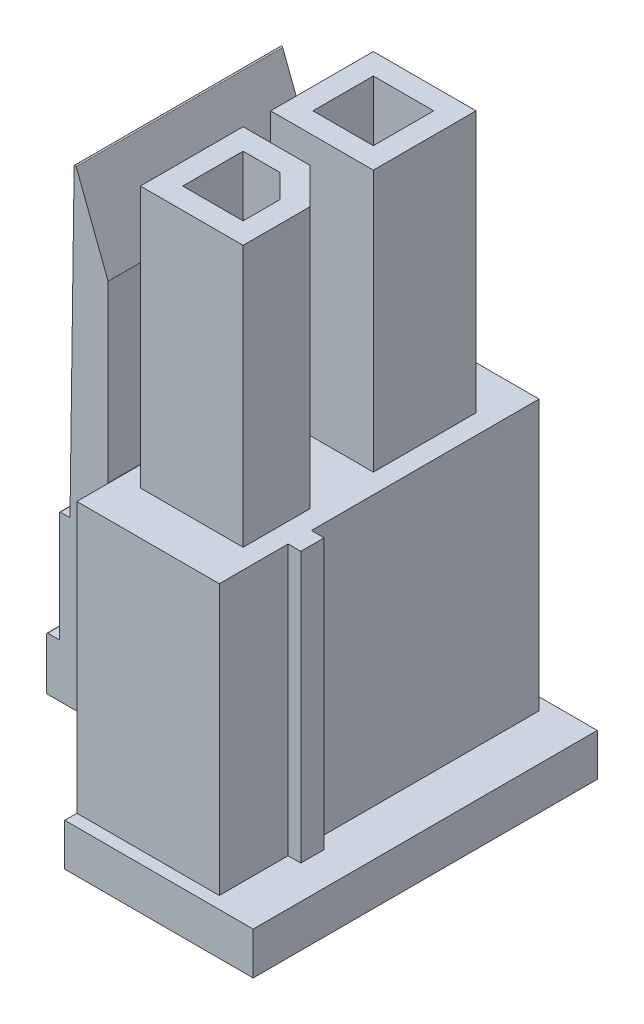
SolidWorks part; units mm, degrees
ref_plane "Front Plane" through (0, 0, 0) normal (0, 0, 1) x (1, 0, 0)
ref_plane "Top Plane" through (0, 0, 0) normal (0, 1, 0) x (1, 0, 0)
ref_plane "Right Plane" through (0, 0, 0) normal (1, 0, 0) x (0, 0, -1)
sketch "Sketch1" plane through (0, 0, 0) normal (0, 0, 1) x (1, 0, 0)
  line L0 (0, 0) -> (3.4163, 0)
  line L1 (3.4163, 0) -> (3.4163, 6.477)
  line L2 (3.4163, 6.477) -> (0, 6.477)
  line L3 (0, 6.477) -> (0, 0)
  dimension "D1" = 3.4163
  dimension "D2" = 6.477
extrude "Extrude1" add sketch "Sketch1" along normal blind 3.8354
mirror "Mirror1" about plane through (0, 0, 3.8354) normal (0, 0, 1) of "Extrude1"
sketch "Sketch2" plane through (3.4163, 0, 0) normal (1, 0, 0) x (0, 0, -1)
  line L0 (-7.6708, 0) -> (0, 0) construction
  line L1 (-6.0198, 0) -> (-5.461, 0)
  line L2 (-6.0198, 0) -> (-6.0198, 6.477)
  line L3 (-6.0198, 6.477) -> (-5.461, 6.477)
  line L4 (-5.461, 0) -> (-5.461, 6.477)
  line L5 (-7.6708, 6.477) -> (0, 6.477) construction
  line L6 (-7.6708, 0) -> (-7.6708, 6.477) construction
  dimension "D1" = 1.651
  dimension "D2" = 0.5588
extrude "Extrude2" add sketch "Sketch2" along normal blind 0.3048
sketch "Sketch3" plane through (0, 0, 0) normal (0, -1, 0) x (1, 0, 0)
  line L0 (0, 7.6708) -> (3.4163, 7.6708) construction
  line L1 (0, -0.2921) -> (4.5212, -0.2921)
  line L2 (0, -0.2921) -> (0, 7.9629)
  line L3 (0, 7.9629) -> (4.5212, 7.9629)
  line L4 (4.5212, -0.2921) -> (4.5212, 7.9629)
  dimension "D1" = 8.255
  dimension "D2" = 4.5212
  dimension "D3" = 0.2921
extrude "Extrude3" add sketch "Sketch3" along normal blind 1.016
sketch "Sketch4" plane through (0, 6.477, 0) normal (0, 1, 0) x (1, 0, 0)
  line L0 (2.4384, -2.9972) -> (0.9906, -2.9972)
  line L1 (2.9464, -6.6294) -> (0.4826, -6.6294)
  line L2 (2.9464, -6.6294) -> (2.9464, -5.0277)
  line L3 (2.0843, -4.1656) -> (0.4826, -4.1656)
  line L4 (0.4826, -6.6294) -> (0.4826, -4.1656)
  line L5 (2.9464, -3.5052) -> (0.4826, -3.5052)
  line L6 (2.9464, -3.5052) -> (2.9464, -1.0414)
  line L7 (2.9464, -1.0414) -> (0.4826, -1.0414)
  line L8 (0.4826, -3.5052) -> (0.4826, -1.0414)
  line L9 (0.9906, -2.9972) -> (0.9906, -1.5494)
  line L10 (0, -7.6708) -> (0, 0) construction
  line L11 (3.4163, 0) -> (0, 0) construction
  line L12 (2.9464, -5.0277) -> (2.0843, -4.1656)
  line L13 (2.4384, -1.5494) -> (0.9906, -1.5494)
  line L14 (2.4384, -2.9972) -> (2.4384, -1.5494)
  line L15 (0.9906, -6.1214) -> (0.9906, -4.6736)
  line L16 (1.8739, -4.6736) -> (0.9906, -4.6736)
  line L17 (2.4384, -5.2381) -> (1.8739, -4.6736)
  line L18 (2.4384, -6.1214) -> (2.4384, -5.2381)
  line L19 (2.4384, -6.1214) -> (0.9906, -6.1214)
  dimension "D1" = 5.588
  dimension "D2" = 2.4638
  dimension "D3" = 2.4638
  dimension "D4" = 0.4826
  dimension "D5" = 1.0414
  dimension "D6" = 1.2192
  dimension "D7" = 0.508
extrude "Extrude4" add sketch "Sketch4" along normal blind 6.2738
sketch "Sketch5" plane through (0, -1.016, 0) normal (0, -1, 0) x (1, 0, 0)
  line L0 (0, -0.2921) -> (4.5212, -0.2921) construction
  line L1 (3.0988, 6.5659) -> (0.635, 6.5659)
  line L2 (3.0988, 6.5659) -> (3.0988, 4.0513)
  line L3 (3.0988, 1.1049) -> (0.635, 1.1049)
  line L4 (0.635, 6.5659) -> (0.635, 4.0513)
  line L6 (3.0988, 4.0513) -> (0.635, 4.0513)
  line L7 (3.0988, 3.6195) -> (0.635, 3.6195)
  line L8 (3.0988, 3.6195) -> (3.0988, 1.1049)
  line L9 (0.635, 3.6195) -> (0.635, 1.1049)
  line L10 (4.5212, -0.2921) -> (4.5212, 7.9629) construction
  dimension "D1" = 5.461
  dimension "D2" = 1.397
  dimension "D3" = 1.4224
  dimension "D4" = 2.4638
  dimension "D5" = 2.5146
  dimension "D6" = 2.5146
extrude "Extrude5" cut sketch "Sketch5" against normal blind 7.2898
ref_plane "Plane1" through (0, 0, 3.8354) normal (0, 0, 1) x (1, 0, 0)
sketch "Sketch6" plane through (0, 0, 3.8354) normal (0, 0, 1) x (1, 0, 0)
  line L0 (4.5212, -1.016) -> (0, -1.016) construction
  line L1 (-2.0574, 0.762) -> (-0.635, 0.762)
  line L2 (-2.0828, 0.7874) -> (-2.0828, 2.0066)
  line L5 (0, 6.477) -> (0, 0) construction
  line L6 (-2.0828, 0.762) -> (-2.0828, 2.032)
  line L7 (-2.0574, 2.032) -> (-1.8034, 2.032)
  line L8 (-1.778, 2.0574) -> (-1.778, 4.6736)
  line L9 (-1.7526, 4.699) -> (-1.5491, 4.699)
  line L10 (-1.5237, 4.7241) -> (-1.4246, 12.0555)
  line L11 (-1.3755, 12.0642) -> (-0.6113, 10.0698)
  line L12 (-0.6096, 10.0607) -> (-0.6096, 5.8821)
  line L13 (-0.5842, 5.8567) -> (0, 5.8567)
  line L14 (0, 5.8567) -> (0, 4.4343)
  line L15 (0, 4.4343) -> (-0.5842, 4.4343)
  line L16 (-0.6096, 4.4089) -> (-0.6096, 0.7874)
  arc A0 (-2.0828, 2.0066) -> (-2.0574, 2.032) centre (-2.0574, 2.0066) cw
  arc A1 (-1.778, 2.0574) -> (-1.8034, 2.032) centre (-1.8034, 2.0574) cw
  arc A2 (-1.7526, 4.699) -> (-1.778, 4.6736) centre (-1.7526, 4.6736) ccw
  arc A3 (-1.5237, 4.7241) -> (-1.5491, 4.699) centre (-1.5491, 4.7244) cw
  arc A4 (-2.0574, 0.762) -> (-2.0828, 0.7874) centre (-2.0574, 0.7874) cw
  arc A5 (-1.4246, 12.0555) -> (-1.3755, 12.0642) centre (-1.3992, 12.0551) cw
  arc A6 (-0.6113, 10.0698) -> (-0.6096, 10.0607) centre (-0.635, 10.0607) cw
  arc A7 (-0.5842, 5.8567) -> (-0.6096, 5.8821) centre (-0.5842, 5.8821) cw
  arc A8 (-0.6096, 4.4089) -> (-0.5842, 4.4343) centre (-0.5842, 4.4089) cw
  arc A9 (-0.6096, 0.7874) -> (-0.635, 0.762) centre (-0.635, 0.7874) cw
  point P24 (-1.778, 2.032)
  point P27 (-1.778, 4.699)
  point P30 (-1.524, 4.699)
  point P37 (-0.6096, 5.8567)
  point P40 (-0.6096, 4.4343)
  dimension "D1" = 0.0254
  dimension "D3" = 0.0254
  dimension "D2" = 1.778
  dimension "D4" = 0.254
  dimension "D5" = 1.4224
  dimension "D6" = 2.667
  dimension "D7" = 0.254
  dimension "D8" = 0.6096
  dimension "D9" = 0.6096
extrude "Extrude6" add sketch "Sketch6" along normal blind 2.4765 and the other way blind 2.4765 contours A9 L16 A8 L15 L14 L13 A7 L12 A6 L11 A5 L10 A3 L9 A2 L8 A1 L7 A0 L2 A4 L1
